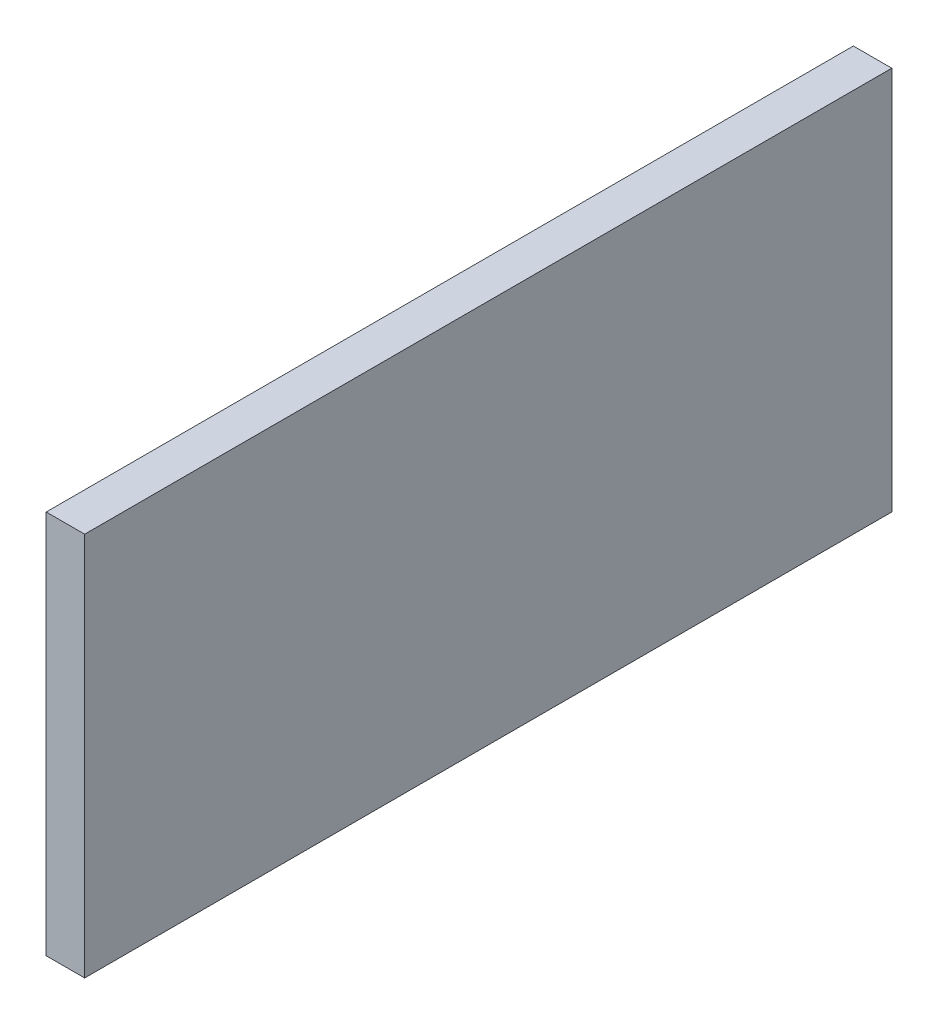
SolidWorks part; units mm, degrees
ref_plane "Front" through (0, 0, 0) normal (0, 0, 1) x (1, 0, 0)
ref_plane "Top" through (0, 0, 0) normal (0, 1, 0) x (1, 0, 0)
ref_plane "Right" through (0, 0, 0) normal (1, 0, 0) x (0, 0, -1)
sketch "Sketch1" plane through (0, 0, 0) normal (0, 1, 0) x (1, 0, 0)
  line L1 (-100, -2100) -> (100, -2100)
  line L2 (-100, -2100) -> (-100, 2100)
  line L3 (-100, 2100) -> (100, 2100)
  line L4 (100, -2100) -> (100, 2100)
  line L5 (-100, -2100) -> (100, 2100) construction
  line L6 (-100, 2100) -> (100, -2100) construction
  point P0 (0, 0)
  dimension "D1" = 200
  dimension "D2" = 4200
extrude "Boss-Extrude1" add sketch "Sketch1" along normal blind 2000
equation "\"D2@Sketch1\"=4000+1*\"D1@Sketch1\""
